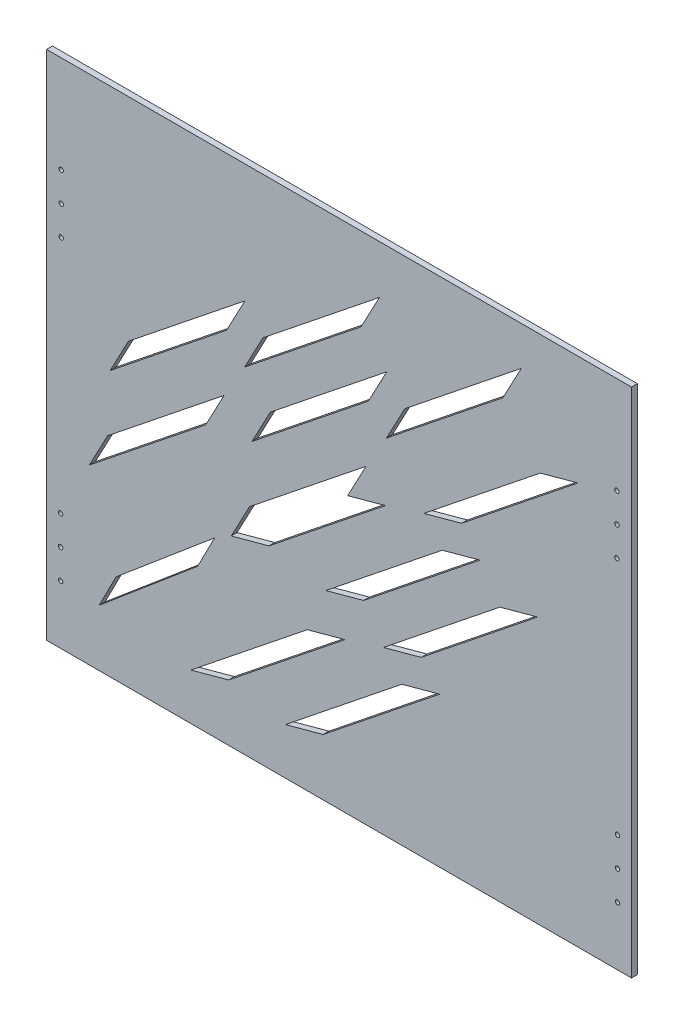
SolidWorks part; units mm, degrees
material "Oak"
ref_plane "Front Plane" through (0, 0, 0) normal (0, 0, 1) x (1, 0, 0)
ref_plane "Top Plane" through (0, 0, 0) normal (0, 1, 0) x (1, 0, 0)
ref_plane "Right Plane" through (0, 0, 0) normal (1, 0, 0) x (0, 0, -1)
sketch "Sketch1" plane through (0, 0, 0) normal (0, 0, 1) x (1, 0, 0)
  line L1 (-200, 175) -> (200, 175)
  line L2 (-200, 175) -> (-200, -175)
  line L3 (-200, -175) -> (200, -175)
  line L4 (200, 175) -> (200, -175)
  circle A0 centre (190.4202, -135) radius 1.5
  circle A1 centre (190.4202, -115) radius 1.5
  circle A2 centre (190.4202, -95) radius 1.5
  circle A3 centre (190, 68.62) radius 1.5
  circle A5 centre (190, 88.62) radius 1.5
  circle A6 centre (190, 108.62) radius 1.5
  circle A7 centre (-190.4202, -135) radius 1.5
  circle A8 centre (-190.4202, -95) radius 1.5
  circle A9 centre (-190.4202, -115) radius 1.5
  circle A10 centre (-190, 68.62) radius 1.5
  circle A11 centre (-190, 88.62) radius 1.5
  circle A12 centre (-190, 108.62) radius 1.5
  point P0 (0, 0)
  dimension "D1" = 400
  dimension "D2" = 350
  dimension "D10" = 10
  dimension "D6" = 3
  dimension "D11" = 3
extrude "Boss-Extrude1" add sketch "Sketch1" along normal blind 4
sketch "Sketch2" plane through (0, 0, 4) normal (0, 0, 1) x (1, 0, 0)
  line L0 (-64.3802, 93.8638) -> (-143.9876, 30.1778)
  line L1 (-64.3802, 93.8638) -> (-76.9244, 70.2228)
  line L2 (-143.9876, 30.1778) -> (-156.5318, 6.5369)
  line L3 (-76.9244, 70.2228) -> (-156.5318, 6.5369)
  line L4 (27.6125, 141.8871) -> (-51.9949, 78.2012)
  line L5 (27.6125, 141.8871) -> (15.0683, 118.2461)
  line L6 (-51.9949, 78.2012) -> (-64.5391, 54.5602)
  line L7 (15.0683, 118.2461) -> (-64.5391, 54.5602)
  line L8 (-78.6013, 30.7662) -> (-158.2087, -32.9197)
  line L9 (-78.6013, 30.7662) -> (-91.1455, 7.1252)
  line L10 (-158.2087, -32.9197) -> (-170.7529, -56.5607)
  line L11 (-91.1455, 7.1252) -> (-170.7529, -56.5607)
  line L12 (32.6196, 100.3477) -> (-46.9878, 36.6618)
  line L13 (32.6196, 100.3477) -> (20.0754, 76.7067)
  line L14 (-46.9878, 36.6618) -> (-59.532, 13.0208)
  line L15 (20.0754, 76.7067) -> (-59.532, 13.0208)
  line L16 (124.6123, 148.371) -> (45.0049, 84.6851)
  line L17 (124.6123, 148.371) -> (112.0681, 124.73)
  line L18 (45.0049, 84.6851) -> (32.4608, 61.0441)
  line L19 (112.0681, 124.73) -> (32.4608, 61.0441)
  line L20 (18.3985, 37.2501) -> (-61.2088, -26.4358)
  line L21 (18.3985, 37.2501) -> (5.8543, 13.6092)
  line L22 (-61.2088, -26.4358) -> (-73.753, -50.0768)
  line L23 (5.8543, 13.6092) -> (-73.753, -50.0768)
  line L24 (-47.9351, -43.028) -> (-73.753, -50.0768)
  line L25 (31.6723, 20.6579) -> (5.8543, 13.6092)
  line L26 (31.6723, 20.6579) -> (-47.9351, -43.028)
  line L27 (137.5802, 92.84) -> (57.9728, 29.1541)
  line L28 (83.7908, 36.2028) -> (57.9728, 29.1541)
  line L29 (163.3981, 99.8887) -> (137.5802, 92.84)
  line L30 (163.3981, 99.8887) -> (83.7908, 36.2028)
  line L31 (70.5346, 13.6327) -> (-9.0728, -50.0532)
  line L32 (16.7452, -43.0045) -> (-9.0728, -50.0532)
  line L33 (96.3526, 20.6814) -> (70.5346, 13.6327)
  line L34 (96.3526, 20.6814) -> (16.7452, -43.0045)
  line L35 (-21.7641, -79.6015) -> (-101.3715, -143.2874)
  line L36 (-75.5535, -136.2387) -> (-101.3715, -143.2874)
  line L37 (4.0539, -72.5528) -> (-21.7641, -79.6015)
  line L38 (4.0539, -72.5528) -> (-75.5535, -136.2387)
  line L39 (109.9618, -0.3707) -> (30.3544, -64.0566)
  line L40 (56.1723, -57.0078) -> (30.3544, -64.0566)
  line L41 (135.7797, 6.6781) -> (109.9618, -0.3707)
  line L42 (135.7797, 6.6781) -> (56.1723, -57.0078)
  line L43 (42.9162, -79.578) -> (-36.6912, -143.2639)
  line L44 (-10.8732, -136.2151) -> (-36.6912, -143.2639)
  line L45 (68.7342, -72.5292) -> (42.9162, -79.578)
  line L46 (68.7342, -72.5292) -> (-10.8732, -136.2151)
  line L47 (-85.1295, -56.8765) -> (-152.4602, -113.6215)
  line L48 (-85.1295, -56.8765) -> (-96.7088, -79.4938)
  line L49 (-152.4602, -113.6215) -> (-164.0395, -136.2387)
  line L50 (-96.7088, -79.4938) -> (-164.0395, -136.2387)
extrude "Cut-Extrude1" cut sketch "Sketch2" against normal blind 10 contours L3 L1 L0 L2 | L7 L5 L4 L6 | L15 L13 L12 L14 | L19 L17 L16 L18 | L30 L29 L27 L28 | L23 L21 L20 L22 | L26 L25 L23 L24 | L42 L41 L39 L40 | L46 L45 L43 L44 | L11 L9 L8 L10 | L31 L32 L34 L33 | L35 L36 L38 L37 | L47 L49 L50 L48
